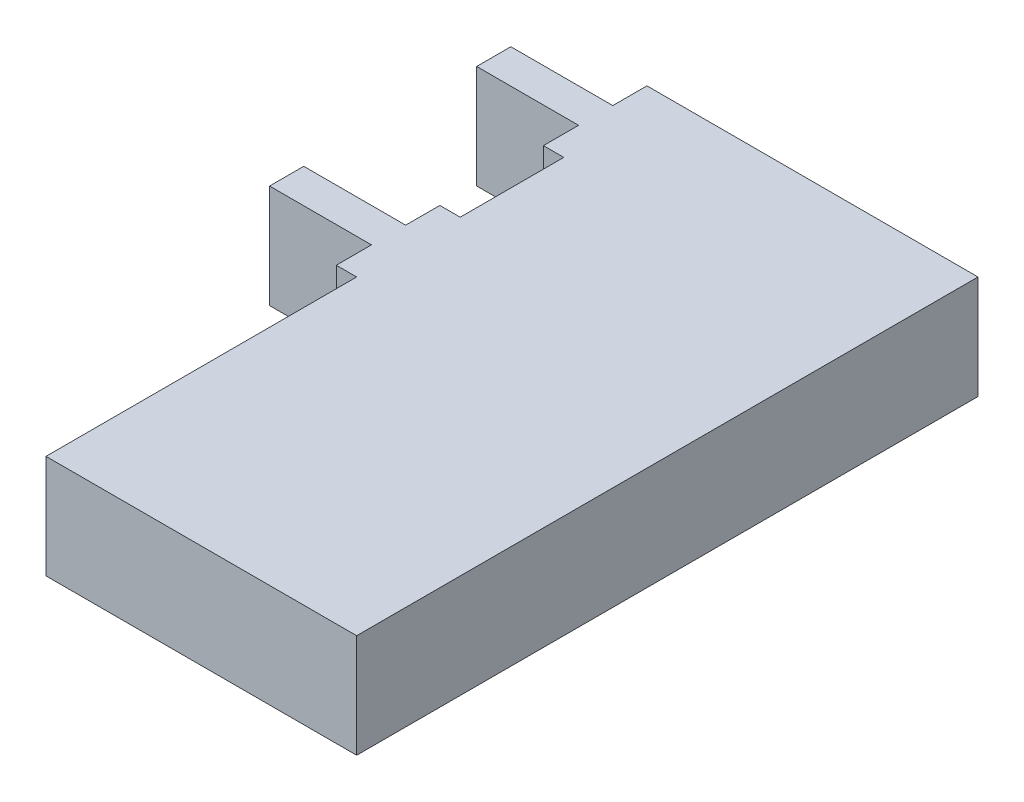
SolidWorks part; units mm, degrees
ref_plane "Front Plane" through (0, 0, 0) normal (0, 0, 1) x (1, 0, 0)
ref_plane "Top Plane" through (0, 0, 0) normal (0, 1, 0) x (1, 0, 0)
ref_plane "Right Plane" through (0, 0, 0) normal (1, 0, 0) x (0, 0, -1)
sketch "Sketch1" plane through (0, 0, 0) normal (0, 1, 0) x (1, 0, 0)
  line L1 (-38.1, -76.2) -> (38.1, -76.2)
  line L2 (-38.1, -76.2) -> (-38.1, 76.2)
  line L3 (-38.1, 76.2) -> (38.1, 76.2)
  line L4 (38.1, -76.2) -> (38.1, 76.2)
  line L5 (-38.1, -76.2) -> (38.1, 76.2) construction
  line L6 (-38.1, 76.2) -> (38.1, -76.2) construction
  point P0 (0, 0)
  dimension "D1" = 76.2
  dimension "D2" = 152.4
extrude "Extrude1" add sketch "Sketch1" along normal blind 25.4
sketch "Sketch2" plane through (-38.1, 0, 0) normal (-1, 0, 0) x (0, 0, 1)
  line L0 (-76.2, 0) -> (76.2, 0) construction
  line L1 (-76.2, 25.4) -> (-50.8, 25.4)
  line L2 (-76.2, 25.4) -> (-76.2, 0)
  line L3 (-76.2, 0) -> (-50.8, 0)
  line L4 (-50.8, 25.4) -> (-50.8, 0)
  dimension "D1" = 25.4
extrude "Extrude2" add sketch "Sketch2" along normal blind 5
sketch "Sketch3" plane through (-43.1, 0, 0) normal (-1, 0, 0) x (0, 0, 1)
  line L0 (-50.8, 25.4) -> (-76.2, 25.4) construction
  line L1 (-67.818, 25.4) -> (-59.436, 25.4)
  line L2 (-67.818, 25.4) -> (-67.818, 0)
  line L3 (-67.818, 0) -> (-59.436, 0)
  line L4 (-59.436, 25.4) -> (-59.436, 0)
  line L5 (-76.2, 0) -> (-50.8, 0) construction
  line L6 (-76.2, 25.4) -> (-76.2, 0) construction
  dimension "D1" = 8.382
  dimension "D2" = 8.382
extrude "Extrude3" add sketch "Sketch3" along normal blind 25
sketch "Sketch4" plane through (-38.1, 0, 0) normal (-1, 0, 0) x (0, 0, 1)
  line L0 (-50.8, 25.4) -> (76.2, 25.4) construction
  line L1 (-25.4, 25.4) -> (0, 25.4)
  line L2 (-25.4, 25.4) -> (-25.4, 0)
  line L3 (-25.4, 0) -> (0, 0)
  line L4 (0, 25.4) -> (0, 0)
  line L5 (-50.8, 0) -> (76.2, 0) construction
  line L6 (76.2, 25.4) -> (76.2, 0) construction
  dimension "D1" = 25.4
  dimension "D2" = 76.2
extrude "Extrude4" add sketch "Sketch4" along normal blind 5
sketch "Sketch5" plane through (-43.1, 0, 0) normal (-1, 0, 0) x (0, 0, 1)
  line L0 (0, 25.4) -> (-25.4, 25.4) construction
  line L1 (-17.018, 25.4) -> (-8.636, 25.4)
  line L2 (-17.018, 25.4) -> (-17.018, 0)
  line L3 (-17.018, 0) -> (-8.636, 0)
  line L4 (-8.636, 25.4) -> (-8.636, 0)
  line L5 (-25.4, 0) -> (0, 0) construction
  line L6 (-25.4, 25.4) -> (-25.4, 0) construction
  dimension "D1" = 8.382
  dimension "D2" = 8.382
extrude "Extrude5" add sketch "Sketch5" along normal blind 25
